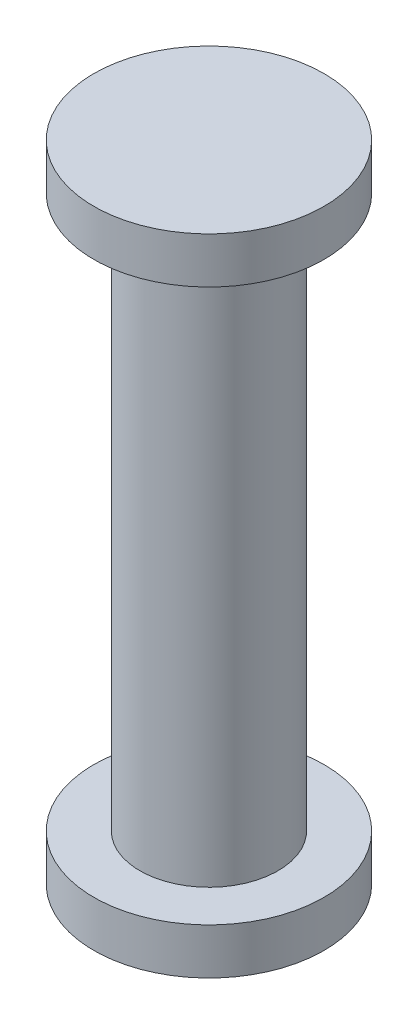
SolidWorks part; units mm, degrees
ref_plane "Front Plane" through (0, 0, 0) normal (0, 0, 1) x (1, 0, 0)
ref_plane "Top Plane" through (0, 0, 0) normal (0, 1, 0) x (1, 0, 0)
ref_plane "Right Plane" through (0, 0, 0) normal (1, 0, 0) x (0, 0, -1)
sketch "Sketch1" plane through (0, 0, 0) normal (0, 0, 1) x (1, 0, 0)
  line L0 (0, 0) -> (0, 14)
  line L1 (0, 14) -> (-2.5, 14)
  line L2 (-2.5, 14) -> (-2.5, 13)
  line L4 (-1.5, 1) -> (-2.5, 1)
  line L5 (-2.5, 1) -> (-2.5, 0)
  line L6 (-2.5, 0) -> (0, 0)
  line L7 (-2.5, 13) -> (-1.5, 13)
  line L8 (-1.5, 13) -> (-1.5, 1)
  dimension "D1" = 14
  dimension "D2" = 1
  dimension "D3" = 2.5
  dimension "D4" = 1.5
revolve "Revolve1" add sketch "Sketch1" angle 360 about L0
